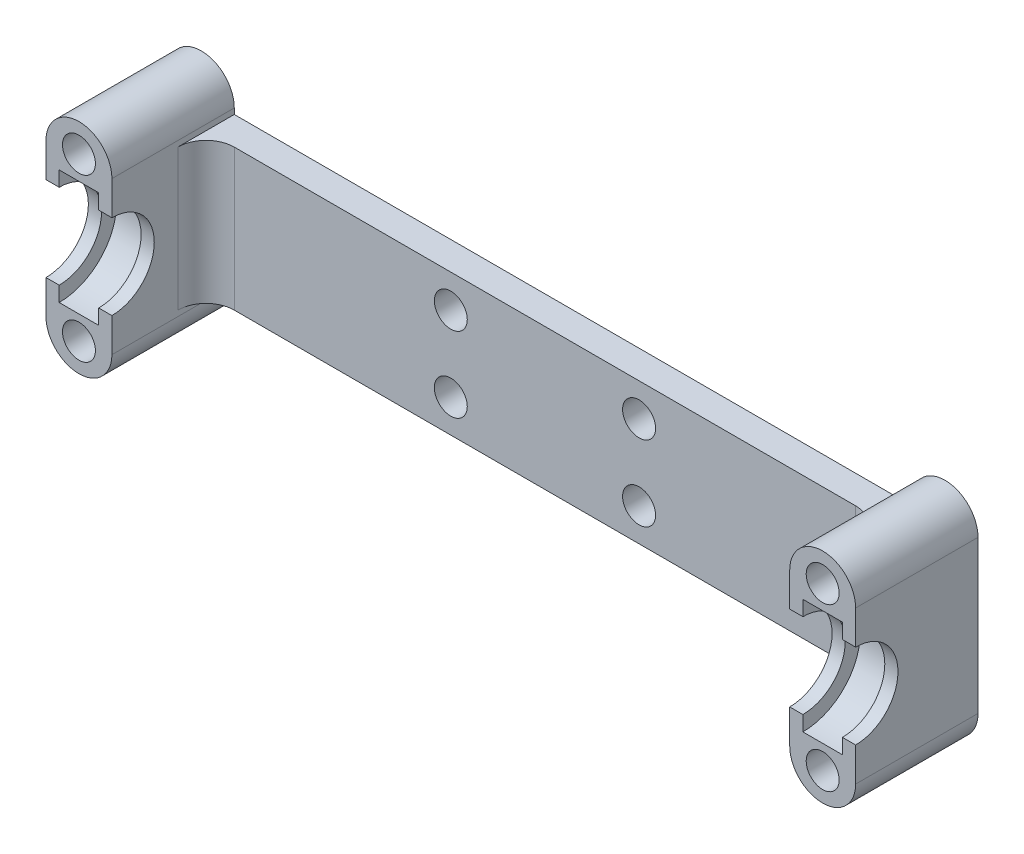
SolidWorks part; units mm, degrees
ref_plane "Front Plane" through (0, 0, 0) normal (0, 0, 1) x (1, 0, 0)
ref_plane "Top Plane" through (0, 0, 0) normal (0, 1, 0) x (1, 0, 0)
ref_plane "Right Plane" through (0, 0, 0) normal (1, 0, 0) x (0, 0, -1)
sketch "Sketch1" plane through (0, 0, 0) normal (0, 0, 1) x (1, 0, 0)
  line L1 (-43, 7.5) -> (43, 7.5)
  line L2 (-43, 7.5) -> (-43, -7.5)
  line L3 (-43, -7.5) -> (43, -7.5)
  line L4 (43, 7.5) -> (43, -7.5)
  line L5 (-43, 7.5) -> (43, -7.5) construction
  line L6 (-43, -7.5) -> (43, 7.5) construction
  point P0 (0, 0)
  dimension "D1" = 15
  dimension "D2" = 86
extrude "Boss-Extrude1" add sketch "Sketch1" along normal blind 3
sketch "Sketch2" plane through (0, 0, 3) normal (0, 0, 1) x (1, 0, 0)
  line L0 (-43, -7.5) -> (43, -7.5) construction
  line L1 (-43, 7.5) -> (-36, 7.5)
  line L2 (-43, 7.5) -> (-43, -7.5)
  line L3 (-43, -7.5) -> (-36, -7.5)
  line L4 (-36, 7.5) -> (-36, -7.5)
  line L6 (43, 7.5) -> (36, 7.5)
  line L7 (43, 7.5) -> (43, -7.5)
  line L8 (43, -7.5) -> (36, -7.5)
  line L9 (36, 7.5) -> (36, -7.5)
  dimension "D1" = 7
  dimension "D2" = 7
extrude "Boss-Extrude2" add sketch "Sketch2" along normal blind 10
sketch "Sketch5" plane through (43, 0, 0) normal (1, 0, 0) x (0, 0, -1)
  line L0 (-13, -7.5) -> (-13, 7.5) construction
  circle A0 centre (-13, 0) radius 4.5
  dimension "D1" = 9
extrude "Cut-Extrude1" cut sketch "Sketch5" against normal through all
ref_plane "Plane1" through (39.5, 0, 0) normal (1, 0, 0) x (0, 0, -1)
sketch "Sketch6" plane through (39.5, 0, 0) normal (1, 0, 0) x (0, 0, -1)
  circle A0 centre (-13, 0) radius 6.1
  dimension "D1" = 12.2
extrude "Cut-Extrude4" cut sketch "Sketch6" against normal blind 2.1 and the other way blind 2.1
sketch "Sketch7" plane through (0, 0, 0) normal (0, 0, 1) x (1, 0, 0)
  line L0 (43, 7.5) -> (36, 7.5) construction
  line L10 (37.4, 6.1) -> (41.6, 6.1)
  line L11 (41.6, 6.1) -> (41.6, 4.5)
  line L12 (41.6, 4.5) -> (43, 4.5)
  line L13 (43, 4.5) -> (43, 7.5)
  line L14 (43, 7.5) -> (36, 7.5)
  line L15 (36, 7.5) -> (36, 4.5)
  line L16 (36, 4.5) -> (37.4, 4.5)
  line L17 (37.4, 4.5) -> (37.4, 6.1)
  line L18 (37.4, 6.1) -> (41.6, 6.1)
  line L19 (41.6, 6.1) -> (41.6, 4.5)
  line L20 (41.6, 4.5) -> (43, 4.5)
  line L21 (43, 4.5) -> (43, 8.1)
  line L23 (36, 8.1) -> (36, 4.5)
  line L24 (36, 4.5) -> (37.4, 4.5)
  line L25 (37.4, 4.5) -> (37.4, 6.1)
  arc A0 (36, 8.1) -> (43, 8.1) centre (39.5, 8.1) cw
  dimension "D2" = 3.5
  dimension "D3" = 0.6
  dimension "D1" = 0
extrude "Boss-Extrude3" add sketch "Sketch7" along normal blind 13
sketch "Sketch8" plane through (0, 0, 13) normal (0, 0, 1) x (1, 0, 0)
  line L0 (39.5, 11.6) -> (39.5, 8.6) construction
  circle A0 centre (39.5, 8.6) radius 1.75
  arc A1 (43, 8.1) -> (36, 8.1) centre (39.5, 8.1) ccw construction
  point P3 (39.5, 8.2311)
  point P5 (39.5, 8.4822)
  dimension "D1" = 3.5
  dimension "D2" = 3
extrude "Cut-Extrude5" cut sketch "Sketch8" against normal through all both and the other way through all
sketch "Sketch9" plane through (0, 0, 3) normal (0, 0, 1) x (1, 0, 0)
  circle A0 centre (-10, -4) radius 1.75
  point P5 (0, 0)
  dimension "D3" = 3.5
  dimension "D1" = 10
  dimension "D2" = 4
extrude "Cut-Extrude6" cut sketch "Sketch9" against normal through all
mirror "Mirror1" about plane through (0, 0, 0) normal (1, 0, 0) of "Cut-Extrude6", "Cut-Extrude5", "Boss-Extrude3", "Cut-Extrude4" second plane through (0, 0, 0) second plane normal (0, 1, 0)
fillet "Fillet1" radius 3 2 edges at (36, 0, 3) (-36, 0, 3)
